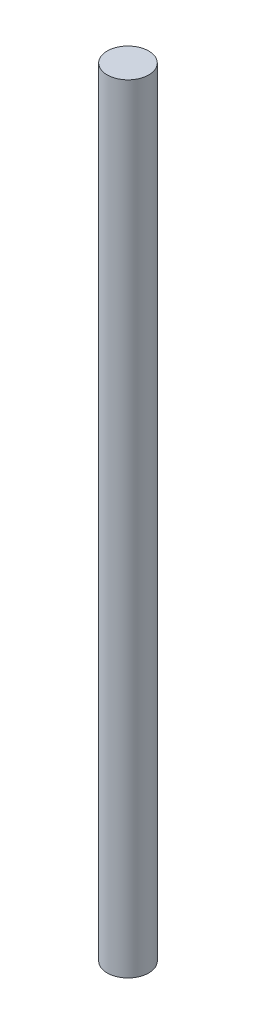
SolidWorks part; units mm, degrees
ref_plane "Alzado" through (0, 0, 0) normal (0, 0, 1) x (1, 0, 0)
ref_plane "Planta" through (0, 0, 0) normal (0, 1, 0) x (1, 0, 0)
ref_plane "Vista lateral" through (0, 0, 0) normal (1, 0, 0) x (0, 0, -1)
sketch "Croquis1" plane through (0, 0, 0) normal (0, 1, 0) x (1, 0, 0)
  circle A0 centre (0, 0) radius 4
  dimension "D1" = 8
extrude "Saliente-Extruir1" add sketch "Croquis1" along normal blind 150
